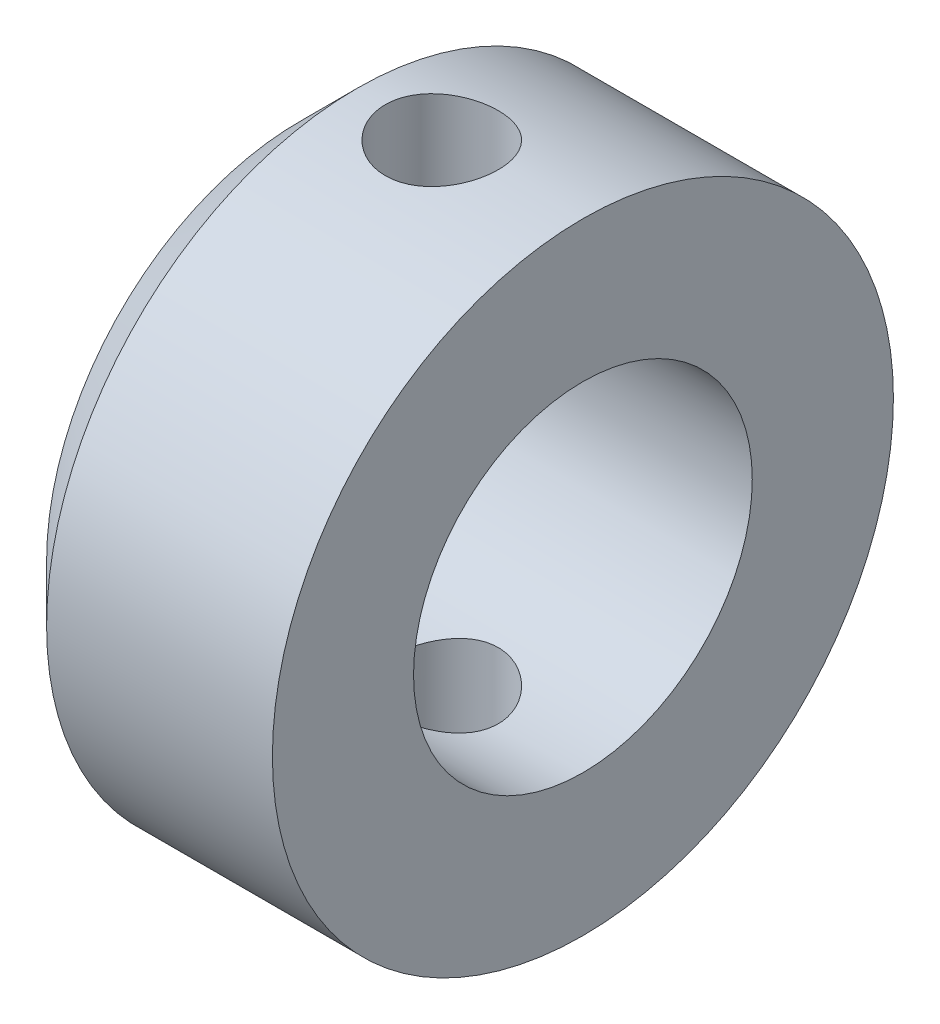
SolidWorks part; units mm, degrees
material "Q235A"
ref_plane "前视基准面" through (0, 0, 0) normal (0, 0, 1) x (1, 0, 0)
ref_plane "上视基准面" through (0, 0, 0) normal (0, 1, 0) x (1, 0, 0)
ref_plane "右视基准面" through (0, 0, 0) normal (1, 0, 0) x (0, 0, -1)
sketch "草图1" plane through (0, 0, 0) normal (0, 0, 1) x (1, 0, 0)
  line L0 (0, 0) -> (-37.1241, 0) construction
  line L1 (0, 0) -> (0, 11)
  line L2 (0, 11) -> (-10, 11)
  line L3 (-10, 11) -> (-10, 0)
  line L4 (0, 0) -> (-10, 0)
  dimension "D1" = 22
  dimension "D2" = 10
revolve "旋转1" add sketch "草图1" angle 360 about L0
chamfer "倒角1" distance 2 angle 45 1 edges at (-10, 0, -11)
sketch "草图2" plane through (-10, 0, 0) normal (-1, 0, 0) x (0, 0, 1)
  circle A0 centre (0, 0) radius 6
  dimension "D1" = 12
extrude "切除-拉伸1" cut sketch "草图2" against normal through all
sketch "草图3" plane through (0, 0, 0) normal (0, 1, 0) x (1, 0, 0)
  line L0 (1.1734, 0) -> (-11.6841, 0) construction
  circle A0 centre (-5, 0) radius 2
  dimension "D2" = 4
  dimension "D1" = 5
extrude "切除-拉伸2" cut sketch "草图3" against normal through all and the other way through all
